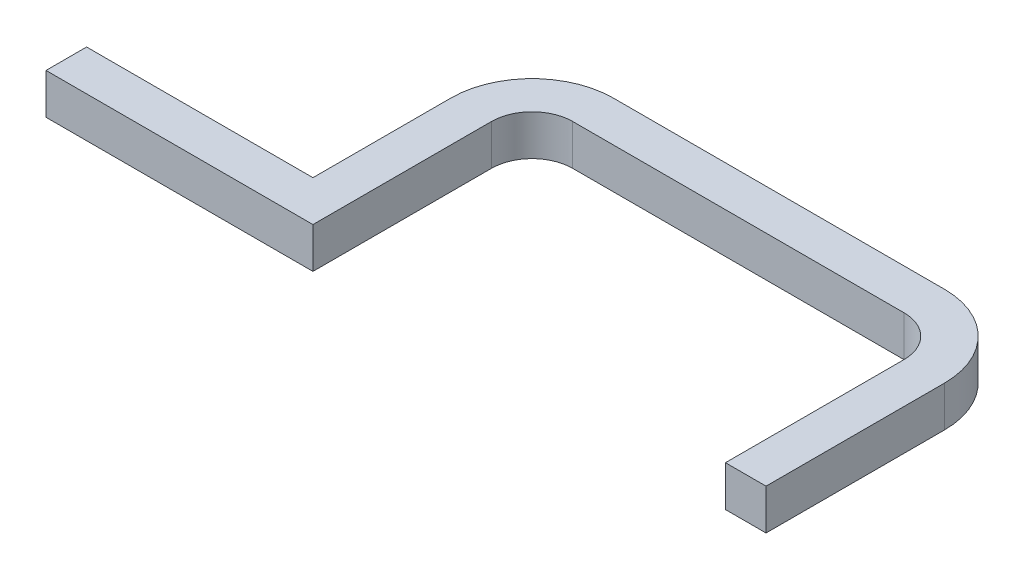
SolidWorks part; units mm, degrees
ref_plane "Front Plane" through (0, 0, 0) normal (0, 0, 1) x (1, 0, 0)
ref_plane "Top Plane" through (0, 0, 0) normal (0, 1, 0) x (1, 0, 0)
ref_plane "Right Plane" through (0, 0, 0) normal (1, 0, 0) x (0, 0, -1)
sketch "Sketch1" plane through (0, 0, 0) normal (0, 1, 0) x (1, 0, 0)
  line L0 (0, 0) -> (29.1496, 0)
  line L1 (29.1496, 0) -> (130.7496, 0) construction
  line L2 (79.9496, 0) -> (79.9496, 53.975) construction
  line L3 (29.1496, 0) -> (29.1496, 43.975)
  line L4 (39.1496, 53.975) -> (120.7496, 53.975)
  line L5 (130.7496, 43.975) -> (130.7496, 0)
  line L6 (0, 10) -> (19.1496, 10)
  line L7 (19.1496, 10) -> (19.1496, 43.975)
  line L8 (39.1496, 63.975) -> (120.7496, 63.975)
  line L9 (140.7496, 43.975) -> (140.7496, 0)
  line L10 (0, 10) -> (-36.6007, 10)
  line L11 (-36.6007, 10) -> (-36.6007, 0)
  line L12 (-36.6007, 0) -> (0, 0)
  line L13 (130.7496, 0) -> (140.7496, 0)
  arc A0 (29.1496, 43.975) -> (39.1496, 53.975) centre (39.1496, 43.975) cw
  arc A1 (120.7496, 53.975) -> (130.7496, 43.975) centre (120.7496, 43.975) cw
  arc A2 (19.1496, 43.975) -> (39.1496, 63.975) centre (39.1496, 43.975) cw
  arc A3 (120.7496, 63.975) -> (140.7496, 43.975) centre (120.7496, 43.975) cw
  dimension "D2" = 53.975
  dimension "D3" = 10
  dimension "D1" = 101.6
  dimension "D4" = 10
extrude "Boss-Extrude1" add sketch "Sketch1" along normal blind 10
